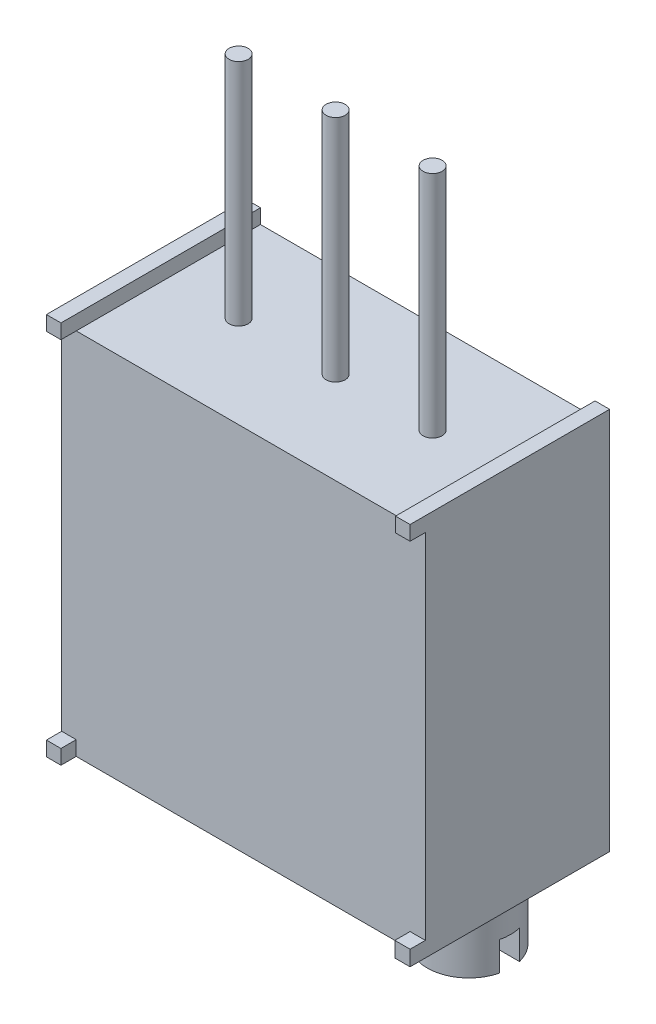
SolidWorks part; units mm, degrees
ref_plane "Alzado" through (0, 0, 0) normal (0, 0, 1) x (1, 0, 0)
ref_plane "Planta" through (0, 0, 0) normal (0, 1, 0) x (1, 0, 0)
ref_plane "Vista lateral" through (0, 0, 0) normal (1, 0, 0) x (0, 0, -1)
sketch "Croquis1" plane through (0, 0, 0) normal (0, 1, 0) x (1, 0, 0)
  line L0 (0, 0) -> (2.54, 0) construction
  line L1 (2.584, 0) -> (2.54, 0) construction
  line L2 (2.54, 0) -> (5.08, 0) construction
  circle A0 centre (0, 0) radius 0.25
  circle A1 centre (2.54, 0) radius 0.25
  circle A2 centre (5.08, 0) radius 0.25
  dimension "D1" = 0.5
  dimension "D3" = 0.5
  dimension "D5" = 0.5
  dimension "D2" = 2.54
  dimension "D4" = 2.54
extrude "Saliente-Extruir1" add sketch "Croquis1" along normal blind 6
sketch "Croquis2" plane through (0, 0, 0) normal (0, 1, 0) x (1, 0, 0)
  line L0 (0, 0) -> (5.08, 0) construction
  line L1 (5.08, 0) -> (5.08, 2.413) construction
  line L2 (2.54, 0) -> (2.54, -0.7875) construction
  line L3 (-2.2225, -0.7875) -> (7.3025, -0.7875) construction
  line L5 (7.3025, -2.413) -> (-2.2225, -2.413)
  line L6 (7.3025, -2.413) -> (7.3025, 2.413)
  line L7 (7.3025, 2.413) -> (-2.2225, 2.413)
  line L8 (-2.2225, -2.413) -> (-2.2225, 2.413)
  line L9 (7.3025, -2.413) -> (-2.2225, 2.413) construction
  line L10 (7.3025, 2.413) -> (-2.2225, -2.413) construction
  dimension "D1" = 2.413
  dimension "D2" = 4.7625
extrude "Saliente-Extruir2" add sketch "Croquis2" against normal blind 9.652
sketch "Croquis3" plane through (0, 0, 0) normal (0, 1, 0) x (1, 0, 0)
  line L0 (-2.2225, 0) -> (-1.8415, 0) construction
  line L1 (-2.2225, 2.413) -> (-2.2225, -2.413) construction
  line L2 (2.54, 0) -> (2.54, -1.1547) construction
  line L3 (-1.8415, 2.413) -> (-2.2225, 2.413)
  line L4 (-1.8415, 2.413) -> (-1.8415, -2.413)
  line L5 (-1.8415, -2.413) -> (-2.2225, -2.413)
  line L6 (-2.2225, 2.413) -> (-2.2225, -2.413)
  line L7 (-1.8415, 2.413) -> (-2.2225, -2.413) construction
  line L8 (-1.8415, -2.413) -> (-2.2225, 2.413) construction
  line L9 (6.9215, -2.413) -> (7.3025, 2.413) construction
  line L10 (6.9215, 2.413) -> (7.3025, -2.413) construction
  line L11 (7.3025, 0) -> (6.9215, 0) construction
  line L12 (7.3025, 2.413) -> (7.3025, -2.413)
  line L13 (6.9215, -2.413) -> (7.3025, -2.413)
  line L14 (6.9215, 2.413) -> (6.9215, -2.413)
  line L15 (6.9215, 2.413) -> (7.3025, 2.413)
  point P5 (-2.032, 0)
  point P21 (7.112, 0)
  dimension "D1" = 0.381
extrude "Saliente-Extruir3" add sketch "Croquis3" along normal blind 0.381
sketch "Croquis4" plane through (0, 0, 2.413) normal (0, 0, 1) x (1, 0, 0)
  line L0 (-1.8415, 0) -> (-2.2225, 0.381) construction
  line L1 (-2.2225, 0.381) -> (-1.8415, 0.381) construction
  line L2 (-1.8415, 0.381) -> (-2.2225, 0) construction
  line L3 (-2.2225, -9.652) -> (-2.2225, 0.381) construction
  line L4 (6.9215, 0.381) -> (7.3025, 0) construction
  line L5 (-1.8415, 0.381) -> (-2.2225, 0.381)
  line L6 (-1.8415, 0.381) -> (-1.8415, 0)
  line L7 (-1.8415, 0) -> (-2.2225, 0)
  line L8 (-2.2225, 0.381) -> (-2.2225, 0)
  line L9 (-1.8415, 0.381) -> (-2.2225, 0) construction
  line L10 (-1.8415, 0) -> (-2.2225, 0.381) construction
  line L11 (6.9215, 0.381) -> (7.3025, 0.381) construction
  line L12 (6.9215, 0.381) -> (6.9215, 0) construction
  line L13 (7.3025, -9.652) -> (7.3025, 0.381) construction
  line L14 (7.3025, 0) -> (6.9215, 0) construction
  line L15 (6.9215, 0) -> (7.3025, 0.381) construction
  line L17 (7.3025, 0.381) -> (6.9215, 0.381)
  line L18 (7.3025, 0.381) -> (7.3025, 0)
  line L19 (7.3025, 0) -> (6.9215, 0)
  line L20 (6.9215, 0.381) -> (6.9215, 0)
  line L21 (7.3025, 0.381) -> (6.9215, 0) construction
  line L22 (7.3025, 0) -> (6.9215, 0.381) construction
  line L23 (-2.2225, -9.652) -> (-1.8415, -9.652)
  line L24 (-2.2225, -9.652) -> (-2.2225, -9.271)
  line L25 (-2.2225, -9.271) -> (-1.8415, -9.271)
  line L26 (-1.8415, -9.652) -> (-1.8415, -9.271)
  line L27 (7.3025, -9.652) -> (6.9025, -9.652)
  line L28 (7.3025, -9.652) -> (7.3025, -9.252)
  line L29 (7.3025, -9.252) -> (6.9025, -9.252)
  line L30 (6.9025, -9.652) -> (6.9025, -9.252)
  point P4 (-2.032, 0.1905)
  point P18 (7.112, 0.1905)
  dimension "D1" = 0.381
  dimension "D2" = 0.381
  dimension "D3" = 0.4
  dimension "D4" = 0.4
extrude "Saliente-Extruir4" add sketch "Croquis4" along normal blind 0.4
sketch "Croquis5" plane through (0, -9.652, 0) normal (0, -1, 0) x (1, 0, 0)
  line L0 (0, 0) -> (7.3025, 0) construction
  line L1 (7.3025, 2.813) -> (7.3025, -2.413) construction
  line L2 (7.3025, 0) -> (7.3025, -1.2165) construction
  line L3 (7.3025, -1.2165) -> (6.0325, -1.2165) construction
  line L4 (6.0325, -1.2165) -> (6.0325, 0) construction
  circle A0 centre (6.0325, 0) radius 1.0922
  dimension "D2" = 2.1844
  dimension "D1" = 1.27
extrude "Saliente-Extruir5" add sketch "Croquis5" along normal blind 1.524
sketch "Croquis6" plane through (0, -11.176, 0) normal (0, -1, 0) x (1, 0, 0)
  line L0 (6.0325, 0) -> (4.9403, 0) construction
  line L2 (7.2885, -0.2633) -> (4.7765, -0.2633)
  line L3 (7.2885, -0.2633) -> (7.2885, 0.2633)
  line L4 (7.2885, 0.2633) -> (4.7765, 0.2633)
  line L5 (4.7765, -0.2633) -> (4.7765, 0.2633)
  line L6 (7.2885, -0.2633) -> (4.7765, 0.2633) construction
  line L7 (7.2885, 0.2633) -> (4.7765, -0.2633) construction
  circle A0 centre (6.0325, 0) radius 1.0922 construction
extrude "Cortar-Extruir1" cut sketch "Croquis6" against normal blind 0.762
